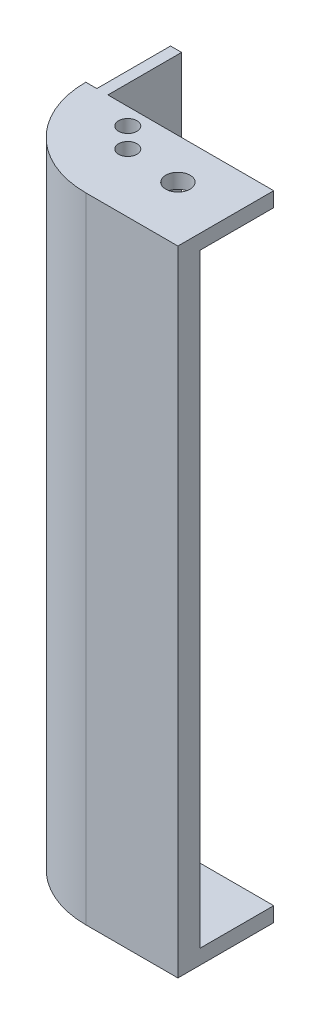
SolidWorks part; units mm, degrees
material "PET"
ref_plane "前视基准面" through (0, 0, 0) normal (0, 0, 1) x (1, 0, 0)
ref_plane "上视基准面" through (0, 0, 0) normal (0, 1, 0) x (1, 0, 0)
ref_plane "右视基准面" through (0, 0, 0) normal (1, 0, 0) x (0, 0, -1)
other "Configuration Table"
sketch "草图1" plane through (0, 0, 0) normal (0, 1, 0) x (1, 0, 0)
  line L1 (-15, 5.5) -> (15, 5.5)
  line L2 (-15, 5.5) -> (-15, -5.5)
  line L3 (-15, -5.5) -> (15, -5.5)
  line L4 (15, 5.5) -> (15, -5.5)
  line L5 (-15, 5.5) -> (15, -5.5) construction
  line L6 (-15, -5.5) -> (15, 5.5) construction
  point P0 (0, 0)
  dimension "D1" = 30
  dimension "D2" = 11
extrude "凸台-拉伸1" add sketch "草图1" along normal blind 6
sketch "草图2" plane through (-15, 0, 0) normal (-1, 0, 0) x (0, 0, 1)
  line L0 (-5.5, 6) -> (-5.5, 0) construction
  line L1 (-13.5, 2) -> (2.5, 2)
  line L2 (-13.5, 2) -> (-13.5, 4)
  line L3 (-13.5, 4) -> (2.5, 4)
  line L4 (2.5, 2) -> (2.5, 4)
  line L5 (-13.5, 2) -> (2.5, 4) construction
  line L6 (-13.5, 4) -> (2.5, 2) construction
  line L7 (-5.5, 6) -> (5.5, 6) construction
  line L8 (5.5, 6) -> (5.5, 0) construction
  point P0 (-5.5, 3)
  dimension "D1" = 2
  dimension "D2" = 3
extrude "切除-拉伸1" cut sketch "草图2" against normal blind 144
sketch "草图3" plane through (0, 6, 0) normal (0, 1, 0) x (1, 0, 0)
  line L0 (2, 5.5) -> (-2, 5.5)
  line L1 (15, 5.5) -> (-15, 5.5) construction
  line L2 (-2, 5.5) -> (-2, -3.5)
  line L3 (-2, -3.5) -> (-15, -3.5)
  line L4 (-15, 5.5) -> (-15, -5.5) construction
  line L5 (-15, -3.5) -> (-15, -5.5)
  line L6 (-15, -5.5) -> (15, -5.5)
  line L7 (-15, -5.5) -> (15, -5.5) construction
  line L8 (0, 5.5) -> (0, -5.5) construction
  line L9 (15, -3.5) -> (15, -5.5)
  line L10 (2, -3.5) -> (15, -3.5)
  line L11 (2, 5.5) -> (2, -3.5)
  dimension "D1" = 2
  dimension "D2" = 2
extrude "凸台-拉伸2" add sketch "草图3" along normal blind 80
sketch "草图4" plane through (0, 6, 0) normal (0, 1, 0) x (1, 0, 0)
  line L0 (-15, 5.5) -> (-15, 2) construction
  line L1 (-15, 5.5) -> (-15, -3.5) construction
  line L2 (-15, 2) -> (15, 2) construction
  line L3 (15, -3.5) -> (15, 5.5) construction
  line L4 (0, 5.5) -> (0, -5.5) construction
  line L5 (2, 5.5) -> (-2, 5.5) construction
  line L6 (-15, -5.5) -> (15, -5.5) construction
  circle A0 centre (-7.5, 2) radius 1.75
  circle A1 centre (7.5, 2) radius 1.75
  point P10 (0, 2)
  dimension "D2" = 7.5
  dimension "D3" = 3.5
  dimension "D1" = 3.5
extrude "切除-拉伸2" cut sketch "草图4" against normal blind 144
sketch "草图5" plane through (-15, 0, 0) normal (-1, 0, 0) x (0, 0, 1)
  line L1 (-5.5, 0) -> (5.5, 0)
  line L2 (-5.5, 0) -> (-5.5, 86)
  line L3 (-5.5, 86) -> (5.5, 86)
  line L4 (5.5, 0) -> (5.5, 86)
extrude "切除-拉伸3" cut sketch "草图5" against normal blind 2.5
sketch "草图6" plane through (0, 6, 0) normal (0, 1, 0) x (1, 0, 0)
  line L0 (-12.5, -2.5) -> (-12.5, 7.5) construction
  line L1 (-22.5, 7.5) -> (-25.5, 7.5)
  line L2 (-12.5, -2.5) -> (-12.5, -5.5)
  arc A0 (-22.5, 7.5) -> (-12.5, -2.5) centre (-12.5, 7.5) ccw
  arc A1 (-25.5, 7.5) -> (-12.5, -5.5) centre (-12.5, 7.5) ccw
  dimension "D1" = 10
extrude "凸台-拉伸3" add sketch "草图6" along normal up to surface and the other way up to surface up to face at (0.625, 86, 1.75) other way up to face at (7.5, 0, -0.25)
sketch "草图7" plane through (0, 0, -7.5) normal (0, 0, -1) x (-1, 0, 0)
  line L0 (25.5, 0) -> (22.5, 0) construction
  line L1 (22.5, 86) -> (24, 86)
  line L2 (22.5, 86) -> (22.5, 0)
  line L3 (22.5, 0) -> (24, 0)
  line L4 (24, 86) -> (24, 0)
  dimension "D1" = 1.5
extrude "凸台-拉伸4" add sketch "草图7" along normal blind 10
sketch "草图8" plane through (-12.5, 0, 0) normal (1, 0, 0) x (0, 0, -1)
  line L1 (-2.5, 86) -> (-26.7009, 86)
  line L2 (-2.5, 86) -> (-2.5, -9.5147)
  line L3 (-2.5, -9.5147) -> (-26.7009, -9.5147)
  line L4 (-26.7009, 86) -> (-26.7009, -9.5147)
  line L5 (-2.5, 86) -> (26.8925, 86)
  line L6 (-2.5, 86) -> (-2.5, -9.5147)
  line L7 (-2.5, -9.5147) -> (26.8925, -9.5147)
  line L8 (26.8925, 86) -> (26.8925, -9.5147)
  line M1 (-3.5, 86) -> (-3.5, 6)
  line M2 (-3.5, 6) -> (-2.5, 6)
  line M3 (-2.5, 6) -> (-2.5, 86)
extrude "切除-拉伸4" cut sketch "草图8" along normal blind 40 contours L8 L5 L2 L7 M3 | L1 L4 L3 L2 M2 M1
sketch "草图9" plane through (0, 86, 0) normal (0, 1, 0) x (1, 0, 0)
  line L0 (-12.5, -2.5) -> (-12.5, 7.5)
  line L1 (-12.5, 7.5) -> (-22.5, 7.5)
  arc A0 (-22.5, 7.5) -> (-12.5, -2.5) centre (-12.5, 7.5) ccw construction
  arc A1 (-22.5, 7.5) -> (-12.5, -2.5) centre (-12.5, 7.5) ccw
extrude "凸台-拉伸5" add sketch "草图9" against normal blind 2
sketch "草图10" plane through (0, 84, 0) normal (0, -1, 0) x (-1, 0, 0)
  line L0 (22.5, 7.5) -> (12.5, -2.5) construction
  line L1 (17.5, 2.5) -> (12.5, 2.5) construction
  line L2 (12.5, -2.5) -> (12.5, 7.5) construction
  line L3 (17.5, 2.5) -> (17.5, 7.5) construction
  line L4 (12.5, 7.5) -> (22.5, 7.5) construction
  circle A0 centre (14.8, 2.5) radius 1.25
  circle A1 centre (17.5, 5.2) radius 1.25
  dimension "D1" = 2.3
  dimension "D2" = 2.3
  dimension "D3" = 2.5
  dimension "D4" = 2.5
extrude "切除-拉伸5" cut sketch "草图10" against normal blind 3
ref_plane "基准面1" through (0, 43, 0) normal (0, -1, 0) x (-1, 0, 0)
mirror "镜向2" about plane through (0, 43, 0) normal (0, -1, 0) of "凸台-拉伸5", "切除-拉伸5"
sketch "草图11" plane through (-12.5, 0, 0) normal (1, 0, 0) x (0, 0, -1)
  line L0 (-5.5, 0) -> (7.5, 0) construction
  line L1 (-5.5, 86) -> (-2.5, 86)
  line L2 (-5.5, 86) -> (-5.5, 0)
  line L3 (-5.5, 0) -> (-2.5, 0)
  line L4 (-2.5, 86) -> (-2.5, 0)
extrude "凸台-拉伸6" add sketch "草图11" along normal blind 12.5
sketch "草图12" plane through (-12.5, 0, 0) normal (1, 0, 0) x (0, 0, -1)
  line L1 (-2.5, 2) -> (7.5, 2)
  line L2 (-2.5, 2) -> (-2.5, 0)
  line L3 (-2.5, 0) -> (7.5, 0)
  line L4 (7.5, 2) -> (7.5, 0)
  line L5 (7.5, 86) -> (-2.5, 86)
  line L6 (7.5, 86) -> (7.5, 84)
  line L7 (7.5, 84) -> (-2.5, 84)
  line L8 (-2.5, 86) -> (-2.5, 84)
extrude "凸台-拉伸7" add sketch "草图12" along normal up to surface (12.5 mm away) up to face at (0, 43, 4)
sketch "草图13" plane through (0, 86, 0) normal (0, 1, 0) x (1, 0, 0)
  line L0 (0, 2) -> (-7.5, 2) construction
  line L1 (0, 7.5) -> (0, -5.5) construction
  line L2 (0, 7.5) -> (-22.5, 7.5) construction
  circle A0 centre (-7.5, 2) radius 1.65
  dimension "D2" = 3.3
  dimension "D1" = 7.5
  dimension "D3" = 5.5
extrude "切除-拉伸6" cut sketch "草图13" against normal blind 100
sketch "草图15" plane through (0, 0, 0) normal (1, 0, 0) x (0, 0, -1)
  line L1 (-2.5, 84) -> (7.5, 84)
  line L2 (-2.5, 84) -> (-2.5, 2)
  line L3 (-2.5, 2) -> (7.5, 2)
  line L4 (7.5, 84) -> (7.5, 2)
